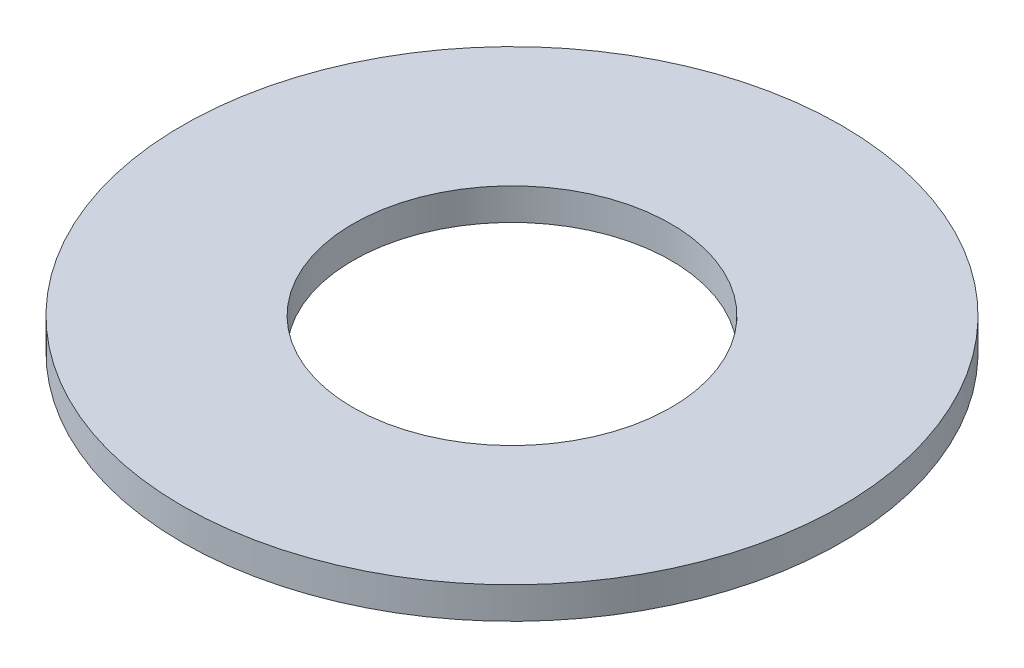
SolidWorks part; units mm, degrees
ref_plane "Front Plane" through (0, 0, 0) normal (0, 0, 1) x (1, 0, 0)
ref_plane "Top Plane" through (0, 0, 0) normal (0, 1, 0) x (1, 0, 0)
ref_plane "Right Plane" through (0, 0, 0) normal (1, 0, 0) x (0, 0, -1)
sketch "Sketch1" plane through (0, 0, 0) normal (0, 1, 0) x (1, 0, 0)
  circle A0 centre (0, 0) radius 66.04
  dimension "D1" = 132.08
extrude "Boss-Extrude1" add sketch "Sketch1" along normal blind 6.35
sketch "Sketch2" plane through (0, 6.35, 0) normal (0, 1, 0) x (1, 0, 0)
  circle A0 centre (0, 0) radius 31.877
  dimension "D1" = 63.754
extrude "Cut-Extrude1" cut sketch "Sketch2" against normal blind 6.35
